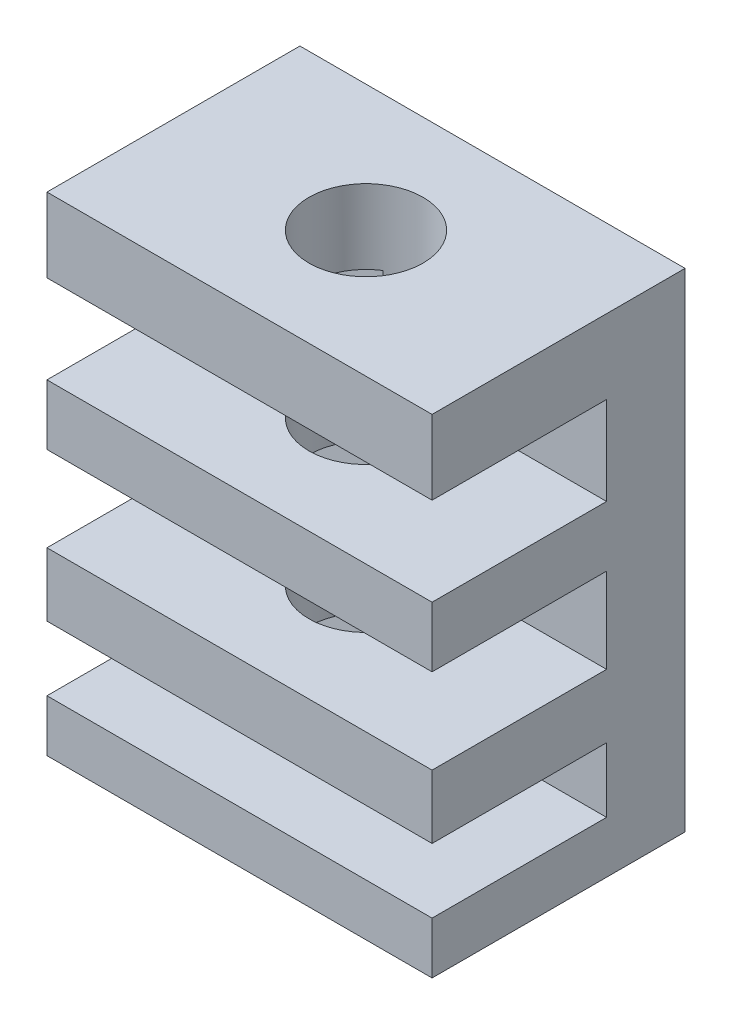
SolidWorks part; units mm, degrees
ref_plane "Front Plane" through (0, 0, 0) normal (0, 0, 1) x (1, 0, 0)
ref_plane "Top Plane" through (0, 0, 0) normal (0, 1, 0) x (1, 0, 0)
ref_plane "Right Plane" through (0, 0, 0) normal (1, 0, 0) x (0, 0, -1)
sketch "Sketch2" plane through (0, 0, 0) normal (1, 0, 0) x (0, 0, -1)
  line L0 (0, 0) -> (0, 25.3478)
  line L1 (0, 25.3478) -> (-13.1367, 25.3478)
  line L2 (-13.1367, 25.3478) -> (-13.1367, 21.4883)
  line L3 (-13.1367, 21.4883) -> (-4.0752, 21.4883)
  line L4 (-4.0752, 21.4883) -> (-4.0752, 16.9016)
  line L5 (-4.0752, 16.9016) -> (-13.1367, 16.9016)
  line L6 (-13.1367, 16.9016) -> (-13.1367, 13.7692)
  line L7 (-13.1367, 13.7692) -> (-4.0752, 13.7692)
  line L8 (-4.0752, 13.7692) -> (-4.0752, 9.3503)
  line L9 (-4.0752, 9.3503) -> (-13.1367, 9.3503)
  line L10 (-13.1367, 9.3503) -> (-13.1367, 6.0501)
  line L11 (-13.1367, 6.0501) -> (-4.0752, 6.0501)
  line L12 (-4.0752, 6.0501) -> (-4.0752, 2.694)
  line L13 (-4.0752, 2.694) -> (-13.1367, 2.694)
  line L14 (-13.1367, 2.694) -> (-13.1367, 0)
  line L15 (-13.1367, 0) -> (0, 0)
extrude "Boss-Extrude2" add sketch "Sketch2" along normal blind 20
sketch "Sketch3" plane through (0, 25.3478, 0) normal (0, 1, 0) x (1, 0, 0)
  circle A0 centre (10, -6.5683) radius 2.9622
extrude "Cut-Extrude1" cut sketch "Sketch3" against normal through all both and the other way through all
